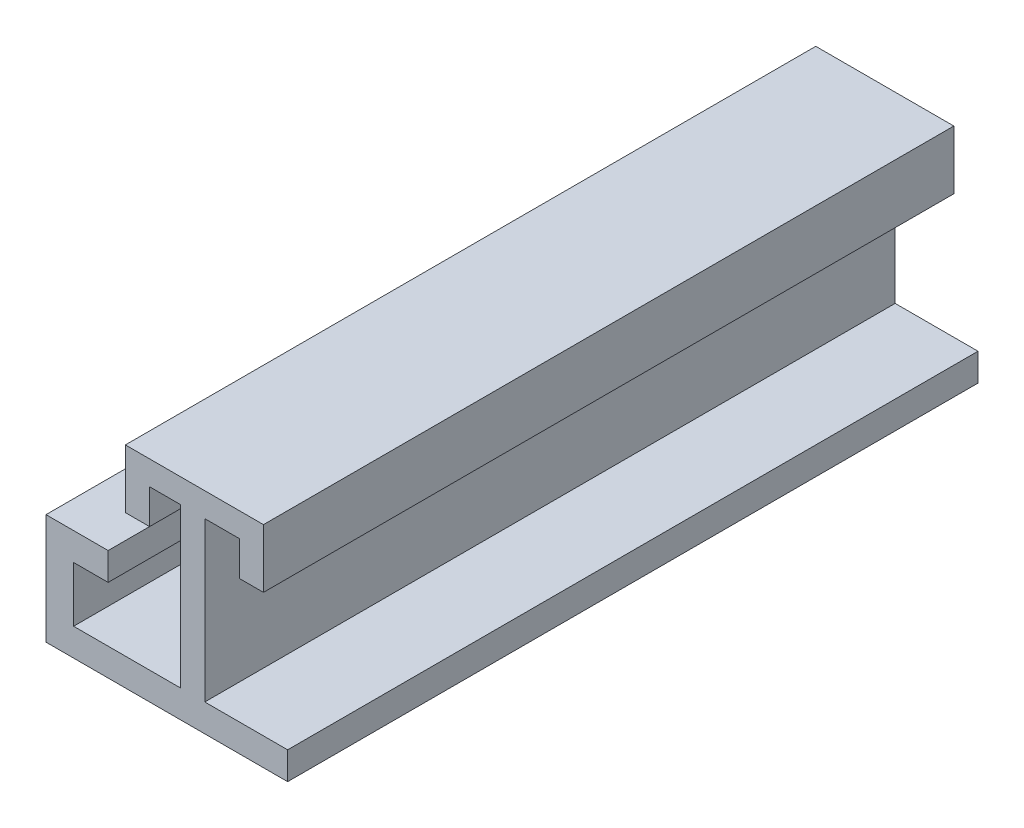
SolidWorks part; units mm, degrees
ref_plane "Спереди" through (0, 0, 0) normal (0, 0, 1) x (1, 0, 0)
ref_plane "Сверху" through (0, 0, 0) normal (0, 1, 0) x (1, 0, 0)
ref_plane "Справа" through (0, 0, 0) normal (1, 0, 0) x (0, 0, -1)
sketch "Эскиз1" plane through (0, 0, 0) normal (0, 0, 1) x (1, 0, 0)
  line L0 (0, 0) -> (0, 50)
  line L1 (0, 50) -> (17, 50)
  line L2 (17, 50) -> (17, 36)
  line L3 (35, 0) -> (-35, 0)
  line L4 (-35, 0) -> (-35, 16)
  line L5 (-35, 16) -> (-25, 16)
  line L6 (35, -4) -> (-39, -4)
  line L7 (0, 50) -> (-17, 50)
  line L8 (-17, 50) -> (-17, 36)
  line L9 (-39, -4) -> (-39, 20)
  line L10 (-39, 20) -> (-25, 20)
  line L11 (13, 46) -> (13, 36)
  line L12 (0, 46) -> (13, 46)
  line L13 (0, 46) -> (-13, 46)
  line L14 (-13, 46) -> (-13, 36)
  line L15 (35, -8) -> (-43, -8)
  line L16 (-43, -8) -> (-43, 24)
  line L17 (-43, 24) -> (-25, 24)
  line L18 (-4, 0) -> (-4, 50)
  line L19 (3, 0) -> (3, 50)
  line L20 (20, 53) -> (20, 36)
  line L21 (0, 53) -> (20, 53)
  line L22 (0, 53) -> (-20, 53)
  line L23 (-20, 53) -> (-20, 36)
  line L24 (-25, 16) -> (-25, 24)
  line L25 (20, 36) -> (13, 36)
  line L26 (-20, 36) -> (-13, 36)
  line L27 (35, 0) -> (35, -8)
  dimension "D1" = 70
  dimension "D2" = 35
  dimension "D3" = 10
  dimension "D4" = 16
  dimension "D5" = 17
  dimension "D6" = 14
  dimension "D7" = 50
  dimension "D8" = 4
  dimension "D9" = 4
  dimension "D10" = 3
  dimension "D11" = 3
extrude "Бобышка-Вытянуть1" add sketch "Эскиз1" along normal mid plane 200 contours L3 L19 L12 L0 | L18 L3 L0 L13 | L23 L26 L8 L7 L1 L2 L25 L20 L21 L22 | L18 L13 L0 L7 | L8 L26 L14 L13 L18 L7 | L25 L2 L1 L19 L12 L11 | L12 L19 L1 L0 | L27 L3 L4 L5 L24 L10 L9 L6 | L27 L6 L9 L10 L24 L17 L16 L15
sketch "Эскиз2" plane through (0, 0, 100) normal (0, 0, 1) x (1, 0, 0)
  line L0 (35, -8) -> (-43, -8) construction
  line L1 (35, 0) -> (27, 0)
  line L2 (35, 0) -> (35, -8)
  line L3 (35, -8) -> (27, -8)
  line L4 (27, 0) -> (27, -8)
  dimension "D1" = 8
extrude "Вырез-Вытянуть1" cut sketch "Эскиз2" against normal through all
